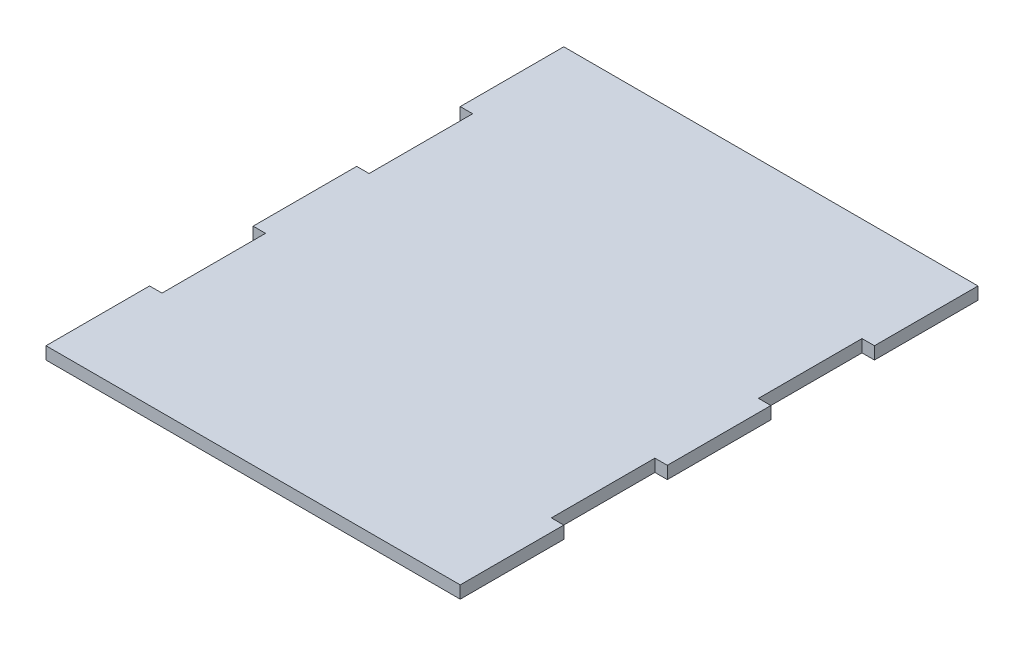
SolidWorks part; units mm, degrees
material "Pine"
ref_plane "Front Plane" through (0, 0, 0) normal (0, 0, 1) x (1, 0, 0)
ref_plane "Top Plane" through (0, 0, 0) normal (0, 1, 0) x (1, 0, 0)
ref_plane "Right Plane" through (0, 0, 0) normal (1, 0, 0) x (0, 0, -1)
sketch "Sketch1" plane through (0, 0, 0) normal (0, 1, 0) x (1, 0, 0)
  line L1 (-100, 125) -> (100, 125)
  line L2 (-100, 125) -> (-100, -125)
  line L3 (-100, -125) -> (100, -125)
  line L4 (100, 125) -> (100, -125)
  line L5 (-100, 125) -> (100, -125) construction
  line L6 (-100, -125) -> (100, 125) construction
  point P0 (0, 0)
  dimension "D1" = 200
  dimension "D2" = 250
extrude "Boss-Extrude1" add sketch "Sketch1" along normal blind 6
sketch "Sketch2" plane through (0, 6, 0) normal (0, 1, 0) x (1, 0, 0)
  line L0 (-100, 125) -> (-100, -125) construction
  line L1 (-100, 75) -> (-94, 75)
  line L2 (-100, 75) -> (-100, 25)
  line L3 (-100, 25) -> (-94, 25)
  line L4 (-94, 75) -> (-94, 25)
  line L5 (100, 125) -> (-100, 125) construction
  line L6 (94, 75) -> (94, 25)
  line L7 (94, 75) -> (100, 75)
  line L8 (100, 75) -> (100, 25)
  line L9 (94, 25) -> (100, 25)
  line L10 (94, -25) -> (94, -75)
  line L11 (94, -25) -> (100, -25)
  line L12 (100, -25) -> (100, -75)
  line L13 (94, -75) -> (100, -75)
  line L14 (-100, -25) -> (-100, -75)
  line L15 (-100, -25) -> (-94, -25)
  line L16 (-94, -25) -> (-94, -75)
  line L17 (-100, -75) -> (-94, -75)
  dimension "D1" = 50
  dimension "D2" = 50
  dimension "D3" = 6
  dimension "D4" = 2
  dimension "D5" = 2
extrude "Cut-Extrude1" cut sketch "Sketch2" against normal blind 6
